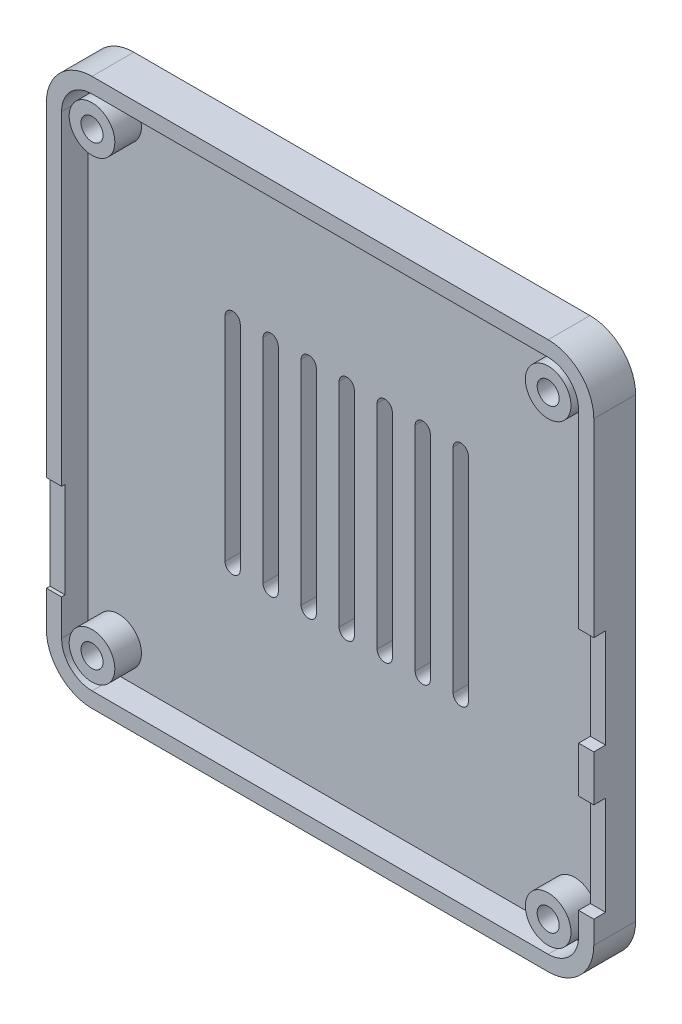
SolidWorks part; units mm, degrees
ref_plane "Front Plane" through (0, 0, 0) normal (0, 0, 1) x (1, 0, 0)
ref_plane "Top Plane" through (0, 0, 0) normal (0, 1, 0) x (1, 0, 0)
ref_plane "Right Plane" through (0, 0, 0) normal (1, 0, 0) x (0, 0, -1)
ref_plane "Z-5_500" through (0, 0, -5.5) normal (0, 0, 1) x (1, 0, 0)
sketch "Sketch1" plane through (0, 0, -5.5) normal (0, 0, 1) x (1, 0, 0)
  line L0 (-30, -36) -> (30, -36)
  line L1 (36, -30) -> (36, 30)
  line L2 (30, 36) -> (-30, 36)
  line L3 (-36, 30) -> (-36, -30)
  arc A0 (30, -36) -> (36, -30) centre (30, -30) ccw
  arc A1 (36, 30) -> (30, 36) centre (30, 30) ccw
  arc A2 (-30, 36) -> (-36, 30) centre (-30, 30) ccw
  arc A3 (-36, -30) -> (-30, -36) centre (-30, -30) ccw
extrude "Boss-Extrude1" add sketch "Sketch1" along normal blind 5.5
ref_plane "Z-3_500" through (0, 0, -3.5) normal (0, 0, 1) x (1, 0, 0)
sketch "Sketch2" plane through (0, 0, -3.5) normal (0, 0, 1) x (1, 0, 0)
  line L0 (-30, -34) -> (30, -34)
  line L1 (34, -30) -> (34, 30)
  line L2 (30, 34) -> (-30, 34)
  line L3 (-34, 30) -> (-34, -30)
  arc A0 (30, -34) -> (34, -30) centre (30, -30) ccw
  arc A1 (34, 30) -> (30, 34) centre (30, 30) ccw
  arc A2 (-30, 34) -> (-34, 30) centre (-30, 30) ccw
  arc A3 (-34, -30) -> (-30, -34) centre (-30, -30) ccw
extrude "Cut-Extrude1" cut sketch "Sketch2" along normal blind 3.5
sketch "Sketch3" plane through (0, 0, -3.5) normal (0, 0, 1) x (1, 0, 0)
  circle A0 centre (-30, 30) radius 3
  circle A1 centre (30, 30) radius 3
  circle A2 centre (-30, -30) radius 3
  circle A3 centre (30, -30) radius 3
extrude "Boss-Extrude2" add sketch "Sketch3" along normal blind 3.5
sketch "Sketch4" plane through (0, 0, -5.5) normal (0, 0, 1) x (1, 0, 0)
  circle A0 centre (-30, 30) radius 1.45
  circle A1 centre (30, 30) radius 1.45
  circle A2 centre (-30, -30) radius 1.45
  circle A3 centre (30, -30) radius 1.45
extrude "Cut-Extrude2" cut sketch "Sketch4" along normal blind 5.5
sketch "Sketch5" plane through (0, 0, -5.5) normal (0, 0, 1) x (1, 0, 0)
  circle A0 centre (-30, 30) radius 2.5
  circle A1 centre (30, 30) radius 2.5
  circle A2 centre (-30, -30) radius 2.5
  circle A3 centre (30, -30) radius 2.5
extrude "Cut-Extrude3" cut sketch "Sketch5" along normal blind 2.6
sketch "Sketch6" plane through (0, 0, -5.5) normal (0, 0, 1) x (1, 0, 0)
  line L0 (-15, -14) -> (-15, 14) construction
  line L1 (-16, -14) -> (-16, 14)
  line L2 (-14, -14) -> (-14, 14)
  line L3 (-10, -14) -> (-10, 14) construction
  line L4 (-11, -14) -> (-11, 14)
  line L5 (-9, -14) -> (-9, 14)
  line L6 (-5, -14) -> (-5, 14) construction
  line L7 (-6, -14) -> (-6, 14)
  line L8 (-4, -14) -> (-4, 14)
  line L9 (0, -14) -> (0, 14) construction
  line L10 (-1, -14) -> (-1, 14)
  line L11 (1, -14) -> (1, 14)
  line L12 (5, -14) -> (5, 14) construction
  line L13 (4, -14) -> (4, 14)
  line L14 (6, -14) -> (6, 14)
  line L15 (10, -14) -> (10, 14) construction
  line L16 (9, -14) -> (9, 14)
  line L17 (11, -14) -> (11, 14)
  line L18 (15, -14) -> (15, 14) construction
  line L19 (14, -14) -> (14, 14)
  line L20 (16, -14) -> (16, 14)
  arc A0 (-16, -14) -> (-14, -14) centre (-15, -14) ccw
  arc A1 (-14, 14) -> (-16, 14) centre (-15, 14) ccw
  arc A2 (-11, -14) -> (-9, -14) centre (-10, -14) ccw
  arc A3 (-9, 14) -> (-11, 14) centre (-10, 14) ccw
  arc A4 (-6, -14) -> (-4, -14) centre (-5, -14) ccw
  arc A5 (-4, 14) -> (-6, 14) centre (-5, 14) ccw
  arc A6 (-1, -14) -> (1, -14) centre (0, -14) ccw
  arc A7 (1, 14) -> (-1, 14) centre (0, 14) ccw
  arc A8 (4, -14) -> (6, -14) centre (5, -14) ccw
  arc A9 (6, 14) -> (4, 14) centre (5, 14) ccw
  arc A10 (9, -14) -> (11, -14) centre (10, -14) ccw
  arc A11 (11, 14) -> (9, 14) centre (10, 14) ccw
  arc A12 (14, -14) -> (16, -14) centre (15, -14) ccw
  arc A13 (16, 14) -> (14, 14) centre (15, 14) ccw
  point P2 (-15, 0)
  point P7 (-10, 0)
  point P14 (-5, 0)
  point P21 (0, 0)
  point P29 (5, 0)
  point P36 (10, 0)
  point P43 (15, 0)
  point P50 (0, 0)
extrude "Cut-Extrude4" cut sketch "Sketch6" along normal blind 2
ref_plane "Z-1_550" through (0, 0, -1.55) normal (0, 0, 1) x (1, 0, 0)
sketch "Sketch7" plane through (0, 0, -1.55) normal (0, 0, 1) x (1, 0, 0)
  line L1 (33.5, -7.95) -> (37, -7.95)
  line L2 (33.5, -7.95) -> (33.5, 5.06)
  line L3 (33.5, 5.06) -> (37, 5.06)
  line L4 (37, -7.95) -> (37, 5.06)
  line L6 (33.5, -27) -> (37, -27)
  line L7 (33.5, -27) -> (33.5, -13.99)
  line L8 (33.5, -13.99) -> (37, -13.99)
  line L9 (37, -27) -> (37, -13.99)
extrude "Cut-Extrude5" cut sketch "Sketch7" along normal blind 1.55
ref_plane "Z-0_465" through (0, 0, -0.465) normal (0, 0, 1) x (1, 0, 0)
sketch "Sketch8" plane through (0, 0, -0.465) normal (0, 0, 1) x (1, 0, 0)
  line L1 (-37, -25.3) -> (-33.5, -25.3)
  line L2 (-37, -25.3) -> (-37, -12.7)
  line L3 (-37, -12.7) -> (-33.5, -12.7)
  line L4 (-33.5, -25.3) -> (-33.5, -12.7)
extrude "Cut-Extrude6" cut sketch "Sketch8" along normal blind 0.465
